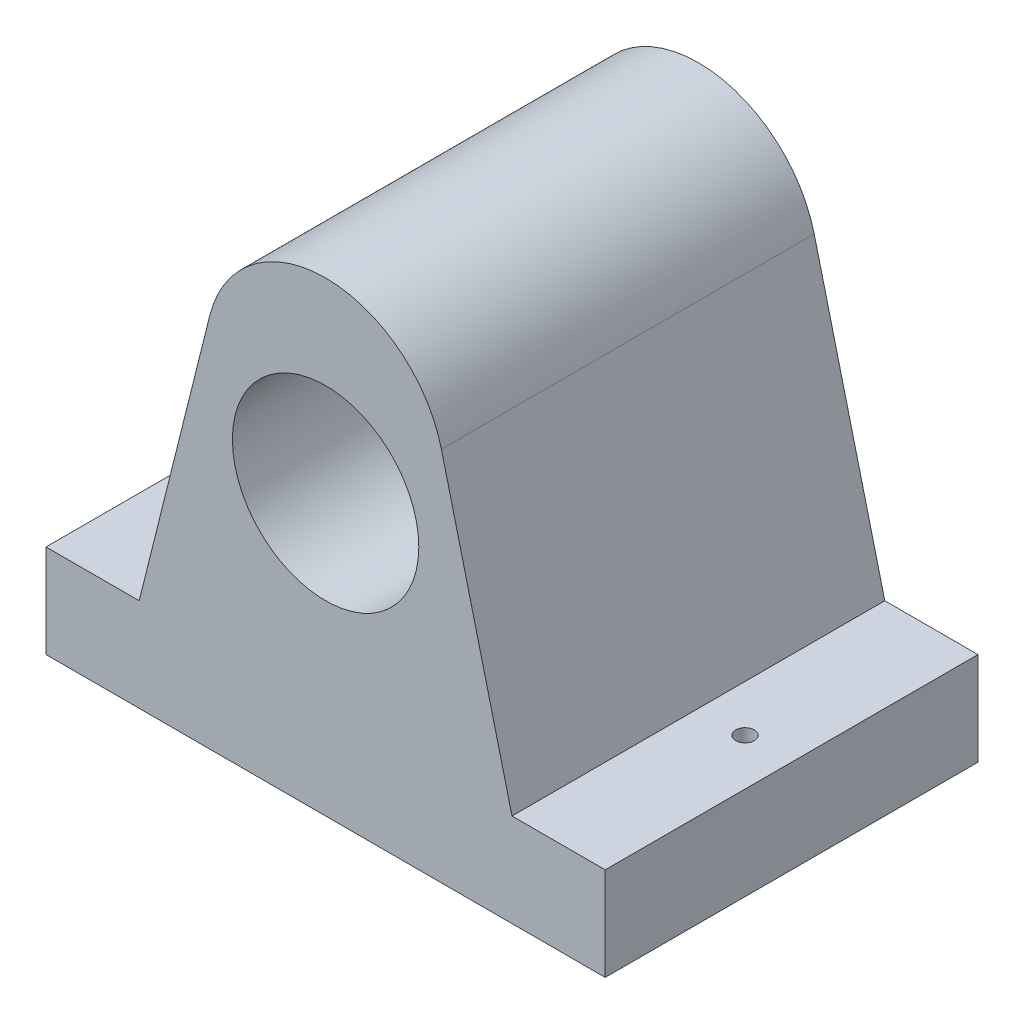
SolidWorks part; units mm, degrees
ref_plane "Front Plane" through (0, 0, 0) normal (0, 0, 1) x (1, 0, 0)
ref_plane "Top Plane" through (0, 0, 0) normal (0, 1, 0) x (1, 0, 0)
ref_plane "Right Plane" through (0, 0, 0) normal (1, 0, 0) x (0, 0, -1)
sketch "Sketch1" plane through (0, 0, 0) normal (0, 0, 1) x (1, 0, 0)
  line L0 (0, 0) -> (300, 0)
  line L1 (0, 0) -> (0, 250)
  line L2 (0, 250) -> (300, 250)
  line L3 (300, 250) -> (300, 0)
  point P5 (0, 0)
  dimension "D1" = 300
  dimension "D2" = 250
  dimension "D3" = 300
  dimension "D4" = 250
extrude "Boss-Extrude1" add sketch "Sketch1" along normal blind 200
sketch "Sketch2" plane through (0, 0, 200) normal (0, 0, 1) x (1, 0, 0)
  line L0 (0, 250) -> (0, 50)
  line L1 (0, 250) -> (0, 0) construction
  line L2 (0, 250) -> (50, 250)
  line L3 (300, 250) -> (0, 250) construction
  line L4 (0, 50) -> (50, 50)
  line L5 (50, 250) -> (50, 50)
extrude "Cut-Extrude1" cut sketch "Sketch2" against normal blind 200
sketch "Sketch3" plane through (0, 0, 200) normal (0, 0, 1) x (1, 0, 0)
  line L0 (300, 250) -> (250, 250)
  line L1 (300, 250) -> (50, 250) construction
  line L2 (250, 250) -> (250, 50)
  line L3 (250, 50) -> (300, 50)
  line L4 (300, 0) -> (300, 250) construction
  line L5 (300, 50) -> (300, 250)
  dimension "D1" = 200
extrude "Cut-Extrude2" cut sketch "Sketch3" against normal blind 200
sketch "Sketch4" plane through (0, 0, 0) normal (0, 0, -1) x (-1, 0, 0)
  line L0 (-50, 250) -> (-100, 250)
  line L1 (-250, 250) -> (-50, 250) construction
  line L2 (-100, 250) -> (-50, 50)
  line L3 (-50, 50) -> (-50, 250)
extrude "Cut-Extrude3" cut sketch "Sketch4" against normal blind 200
sketch "Sketch5" plane through (0, 0, 0) normal (0, 0, -1) x (-1, 0, 0)
  line L0 (-250, 250) -> (-200, 250)
  line L1 (-250, 250) -> (-100, 250) construction
  line L2 (-200, 250) -> (-250, 50)
  line L3 (-250, 250) -> (-250, 50)
extrude "Cut-Extrude4" cut sketch "Sketch5" against normal blind 200
fillet "Fillet1" radius 64.0388 4 edges at (100, 250, 100) (150, 250, 0) (150, 250, 200) (200, 250, 100)
sketch "Sketch6" plane through (0, 0, 0) normal (0, 0, -1) x (-1, 0, 0)
  circle A1 centre (-150, 150) radius 50
extrude "Cut-Extrude5" cut sketch "Sketch6" against normal blind 200
sketch "Sketch8" plane through (0, 50, 0) normal (0, 1, 0) x (1, 0, 0)
  line L0 (0, -100) -> (25, -100)
  line L1 (0, 0) -> (0, -200) construction
  circle A0 centre (25, -100) radius 5
extrude "Cut-Extrude6" cut sketch "Sketch8" against normal blind 200
sketch "Sketch9" plane through (0, 50, 0) normal (0, 1, 0) x (1, 0, 0)
  circle A0 centre (275, -100) radius 5
extrude "Cut-Extrude7" cut sketch "Sketch9" against normal blind 200
